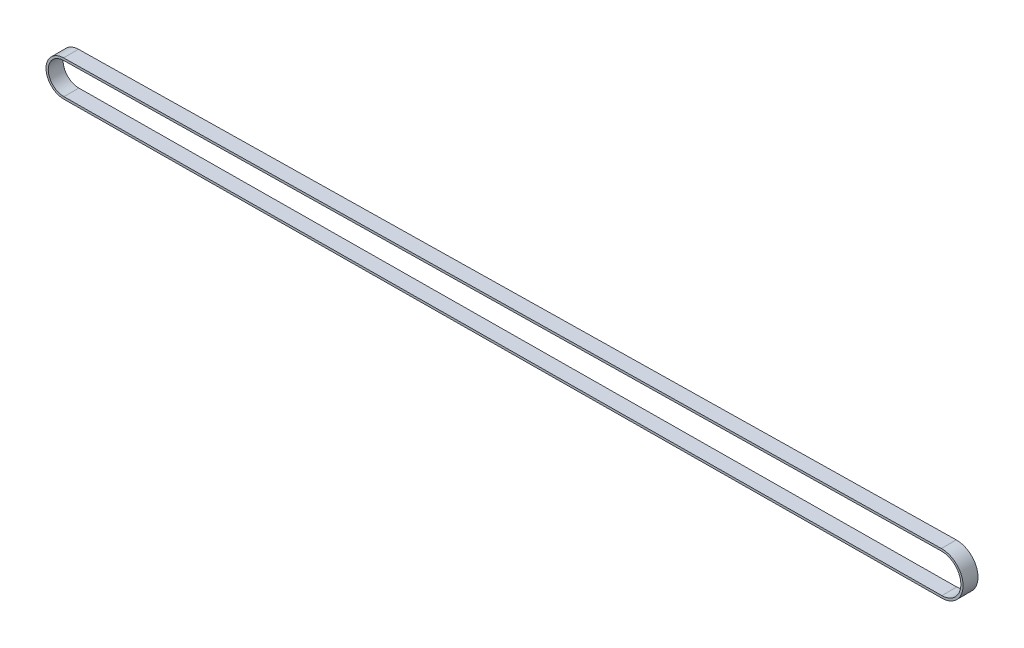
SolidWorks part; units mm, degrees
ref_plane "Front Plane" through (0, 0, 0) normal (0, 0, 1) x (1, 0, 0)
ref_plane "Top Plane" through (0, 0, 0) normal (0, 1, 0) x (1, 0, 0)
ref_plane "Right Plane" through (0, 0, 0) normal (1, 0, 0) x (0, 0, -1)
sketch "Sketch2" plane through (0, 0, 0) normal (0, 0, 1) x (1, 0, 0)
  line L0 (0, 0) -> (1, 0) construction
  line L1 (0, 0) -> (0, 1) construction
  line L2 (0.4146, 0.4) -> (294.6454, 5.094)
  line L3 (294.798, -7.755) -> (0.5386, -10.0492)
  arc A0 (0.5386, -10.0492) -> (0.4146, 0.4) centre (0.4979, -4.8244) cw
  arc A1 (294.6454, 5.094) -> (294.798, -7.755) centre (294.7479, -1.3302) cw
extrude "Extrude-Thin1" add sketch "Sketch2" along normal mid plane 5 thin thin type one direction wall 0.75
